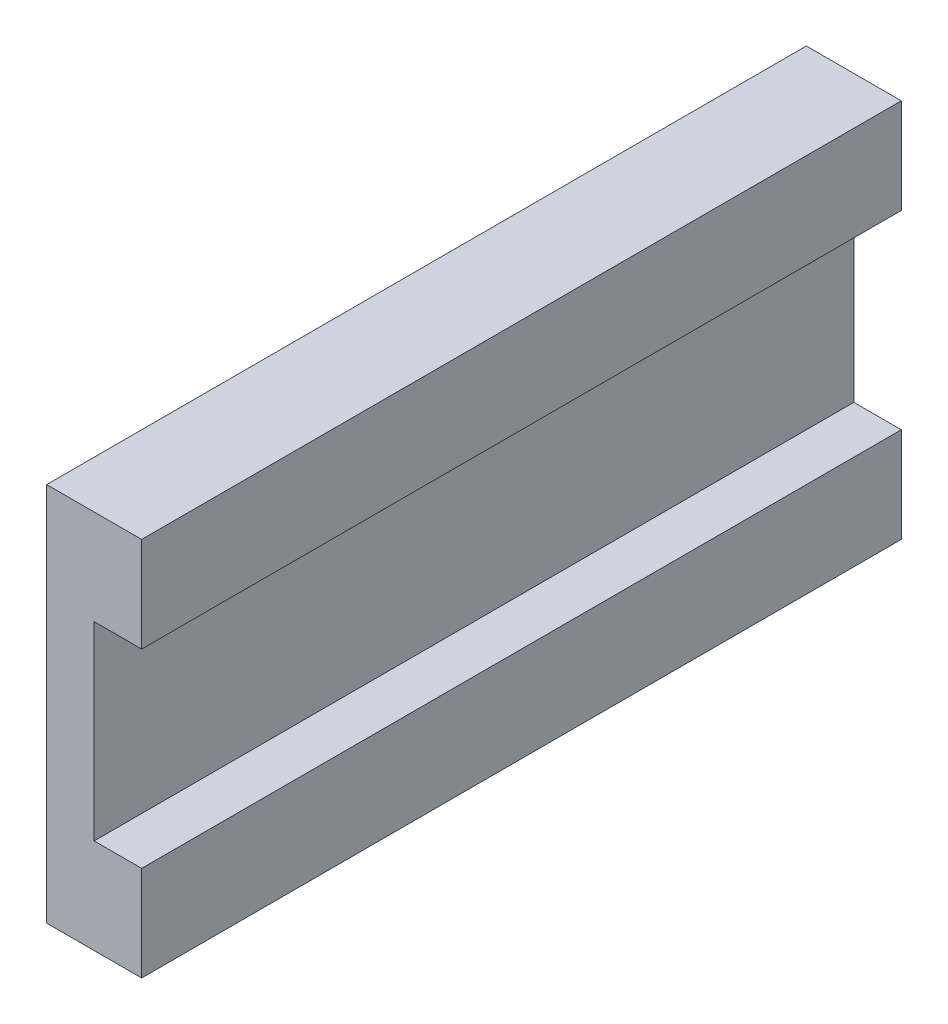
SolidWorks part; units mm, degrees
ref_plane "Front Plane" through (0, 0, 0) normal (0, 0, 1) x (1, 0, 0)
ref_plane "Top Plane" through (0, 0, 0) normal (0, 1, 0) x (1, 0, 0)
ref_plane "Right Plane" through (0, 0, 0) normal (1, 0, 0) x (0, 0, -1)
sketch "Sketch1" plane through (0, 0, 0) normal (0, 0, 1) x (1, 0, 0)
  line L0 (0, 0) -> (0, 80)
  line L1 (0, 80) -> (20, 80)
  line L2 (20, 80) -> (20, 60)
  line L3 (20, 60) -> (10, 60)
  line L4 (10, 60) -> (10, 20)
  line L5 (10, 20) -> (20, 20)
  line L6 (20, 20) -> (20, 0)
  line L7 (20, 0) -> (0, 0)
  dimension "D1" = 20
  dimension "D2" = 80
  dimension "D3" = 20
  dimension "D4" = 20
  dimension "D5" = 40
  dimension "D6" = 10
extrude "Boss-Extrude1" add sketch "Sketch1" along normal mid plane 160
